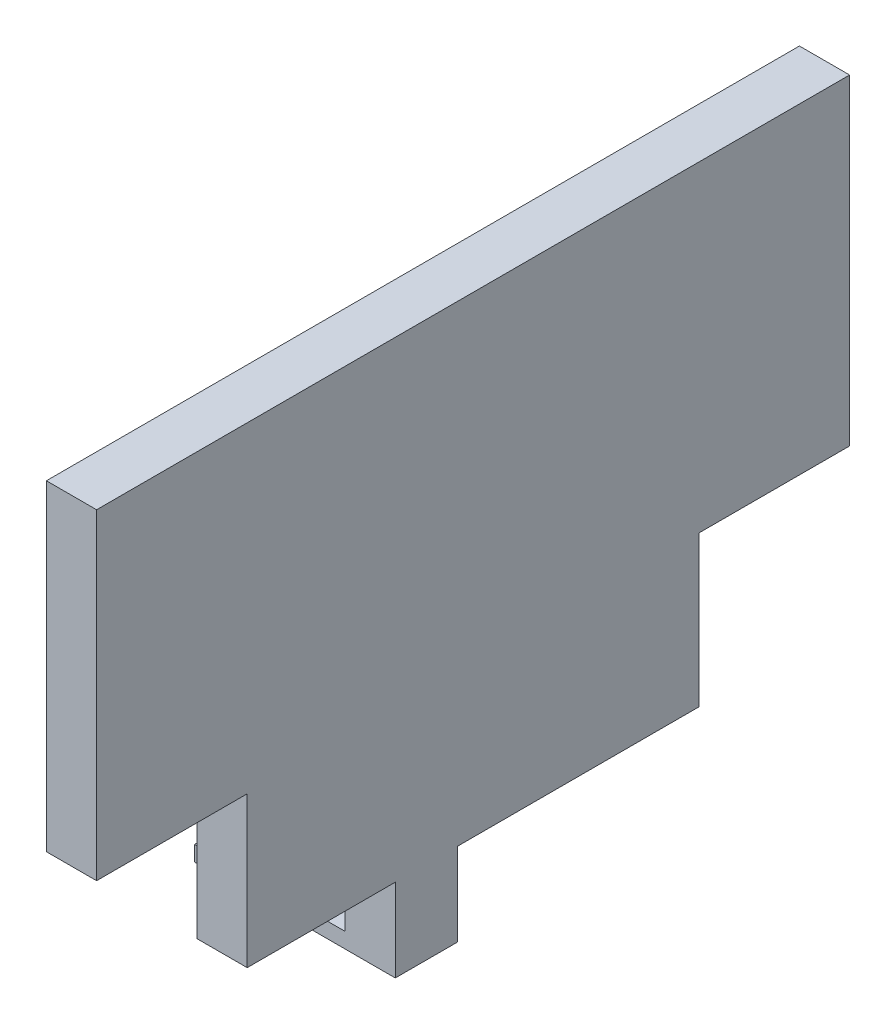
SolidWorks part; units mm, degrees
ref_plane "Front Plane" through (0, 0, 0) normal (0, 0, 1) x (1, 0, 0)
ref_plane "Top Plane" through (0, 0, 0) normal (0, 1, 0) x (1, 0, 0)
ref_plane "Right Plane" through (0, 0, 0) normal (1, 0, 0) x (0, 0, -1)
sketch "Sketch1" plane through (0, 0, 0) normal (0, 0, 1) x (1, 0, 0)
  line L1 (-17.5633, 119.38) -> (-4.8633, 119.38)
  line L2 (-17.5633, 119.38) -> (-17.5633, 0)
  line L3 (-17.5633, 0) -> (-4.8633, 0)
  line L4 (-4.8633, 119.38) -> (-4.8633, 0)
  dimension "D1" = 119.38
  dimension "D2" = 12.7
extrude "Boss-Extrude1" add sketch "Sketch1" along normal blind 190.5
sketch "Sketch2" plane through (-17.5633, 0, 0) normal (-1, 0, 0) x (0, 0, 1)
  line L0 (190.5, 0) -> (190.5, 119.38) construction
  line L1 (190.5, 38.1) -> (152.4, 38.1)
  line L2 (190.5, 38.1) -> (190.5, 0)
  line L3 (190.5, 0) -> (152.4, 0)
  line L4 (152.4, 38.1) -> (152.4, 0)
  line L5 (190.5, 0) -> (0, 0) construction
  line L7 (38.1, 38.1) -> (0, 38.1)
  line L8 (38.1, 38.1) -> (38.1, 0)
  line L9 (38.1, 0) -> (0, 0)
  line L10 (0, 38.1) -> (0, 0)
  dimension "D1" = 38.1
  dimension "D2" = 38.1
  dimension "D3" = 38.1
  dimension "D4" = 38.1
extrude "Cut-Extrude1" cut sketch "Sketch2" against normal through all
sketch "Sketch3" plane through (0, 0, 0) normal (0, -1, 0) x (1, 0, 0)
  line L0 (-17.5633, 152.4) -> (-17.5633, 38.1) construction
  line L1 (-17.5633, 114.9359) -> (-4.8633, 114.9359)
  line L2 (-17.5633, 114.9359) -> (-17.5633, 99.2583)
  line L3 (-17.5633, 99.2583) -> (-4.8633, 99.2583)
  line L4 (-4.8633, 114.9359) -> (-4.8633, 99.2583)
  line L5 (-4.8633, 152.4) -> (-4.8633, 38.1) construction
extrude "Boss-Extrude2" add sketch "Sketch3" along normal up to surface (20.9926 mm away)
sketch "Sketch4" plane through (-17.5633, 0, 0) normal (-1, 0, 0) x (0, 0, 1)
  line L0 (99.2583, -20.9926) -> (99.2583, 0) construction
  line L1 (99.2583, -17.1282) -> (114.9359, -17.1282)
  line L2 (99.2583, -17.1282) -> (99.2583, -20.9926)
  line L3 (99.2583, -20.9926) -> (114.9359, -20.9926)
  line L4 (114.9359, -17.1282) -> (114.9359, -20.9926)
extrude "Boss-Extrude3" add sketch "Sketch4" along normal blind 38.1
